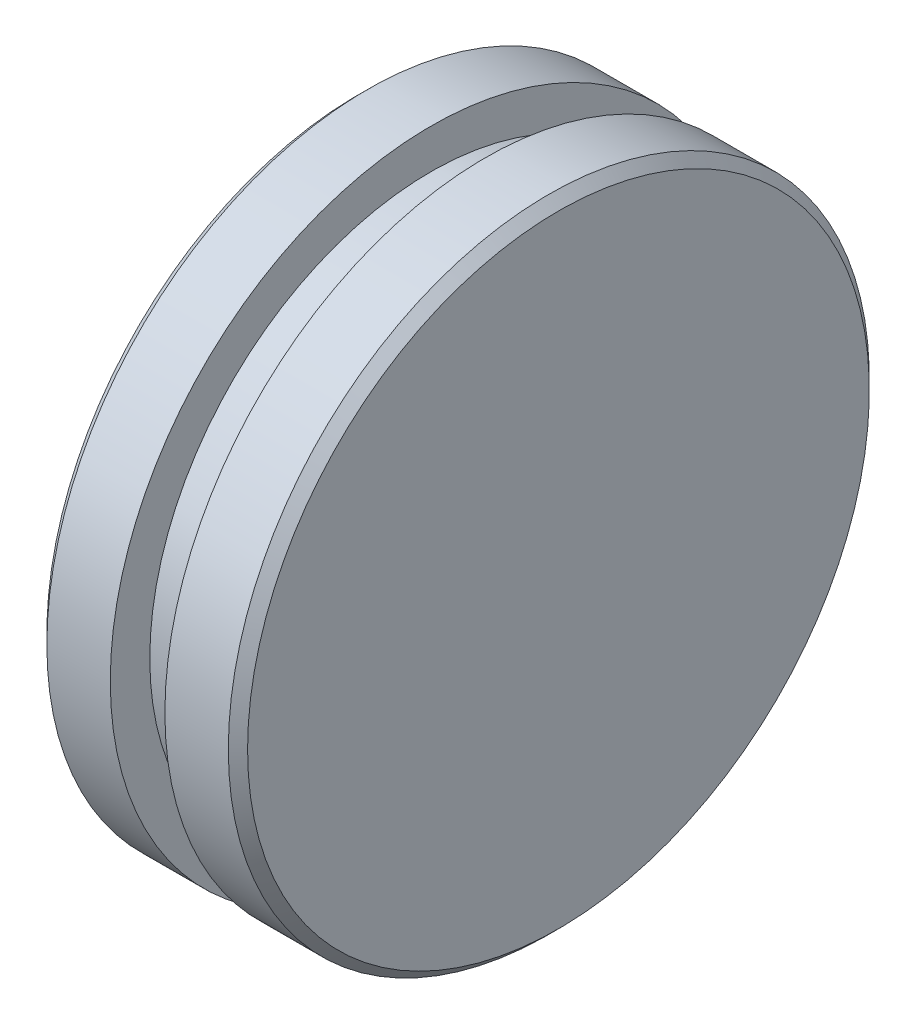
SolidWorks part; units mm, degrees
ref_plane "Alzado" through (0, 0, 0) normal (0, 0, 1) x (1, 0, 0)
ref_plane "Planta" through (0, 0, 0) normal (0, 1, 0) x (1, 0, 0)
ref_plane "Vista lateral" through (0, 0, 0) normal (1, 0, 0) x (0, 0, -1)
sketch "Croquis1" plane through (0, 0, 0) normal (0, 0, 1) x (1, 0, 0)
  line L0 (0, 0.1875) -> (0.55, 0.1875)
  line L1 (0.55, 0.1875) -> (0.55, 0.1)
  line L3 (0.625, 0) -> (0.625, 0.998)
  line L4 (0.625, 0.998) -> (0.3975, 0.998)
  line L5 (0.3975, 0.998) -> (0.3975, 0.875)
  line L6 (0.3975, 0.875) -> (0.2275, 0.875)
  line L7 (0.2275, 0.875) -> (0.2275, 0.998)
  line L8 (0.2275, 0.998) -> (0, 0.998)
  line L9 (0, 0.998) -> (0, 0.1875)
  line L10 (0, 0) -> (0.7959, 0) construction
  line L11 (0.55, 0.1) -> (0.55, 0)
  line L12 (0.55, 0) -> (0.625, 0)
  point P13 (0.625, 0.0112)
  dimension "D1" = 0.998
  dimension "D2" = 0.875
  dimension "D3" = 0.2275
  dimension "D4" = 0.17
  dimension "D5" = 0.625
  dimension "D6" = 0.55
  dimension "D7" = 0.1875
revolve "Revolución1" add sketch "Croquis1" angle 360 about L10
chamfer "Chaflán1" distance 0.03 angle 45 2 edges at (0.625, 0, 0.998) (0, 0, 0.998)
